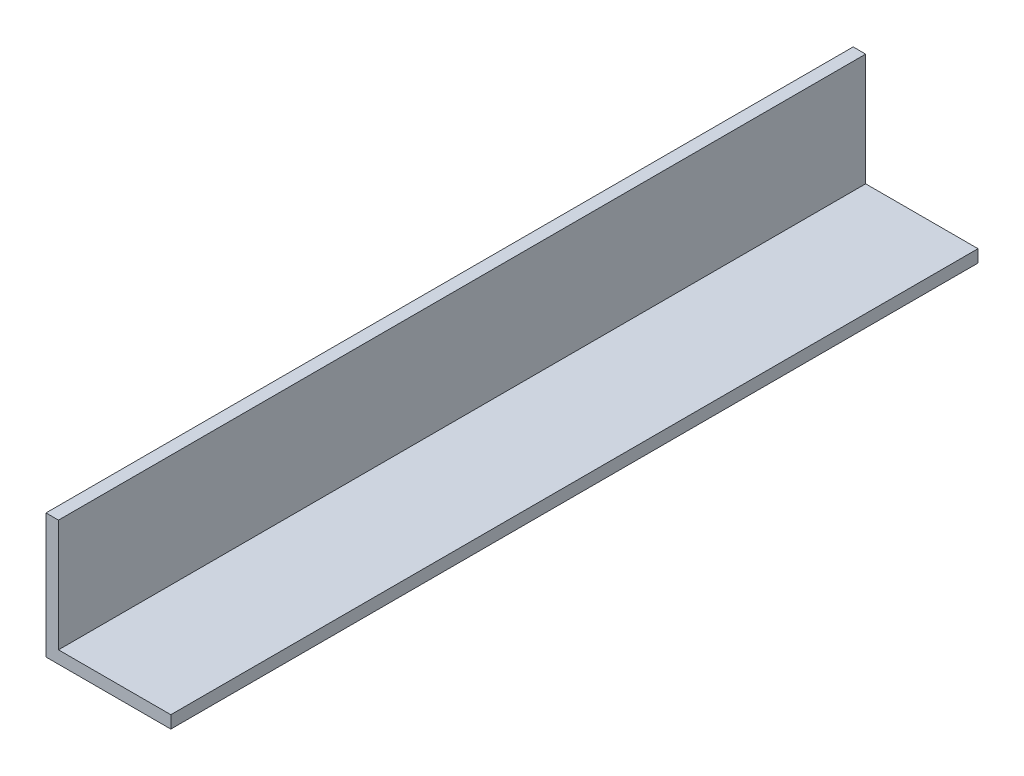
SolidWorks part; units mm, degrees
material "Ferro duttile"
ref_plane "Piano frontale" through (0, 0, 0) normal (0, 0, 1) x (1, 0, 0)
ref_plane "Piano superiore" through (0, 0, 0) normal (0, 1, 0) x (1, 0, 0)
ref_plane "Piano destro" through (0, 0, 0) normal (1, 0, 0) x (0, 0, -1)
sketch "Schizzo1" plane through (0, 0, 0) normal (0, 0, 1) x (1, 0, 0)
  line L0 (0, 0) -> (30, 0)
  line L1 (30, 0) -> (30, 3)
  line L2 (30, 3) -> (3, 3)
  line L3 (3, 3) -> (3, 30)
  line L4 (3, 30) -> (0, 30)
  line L5 (0, 30) -> (0, 0)
  dimension "D1" = 3
  dimension "D2" = 30
extrude "Estrusione-Estrusione1" add sketch "Schizzo1" along normal blind 194
